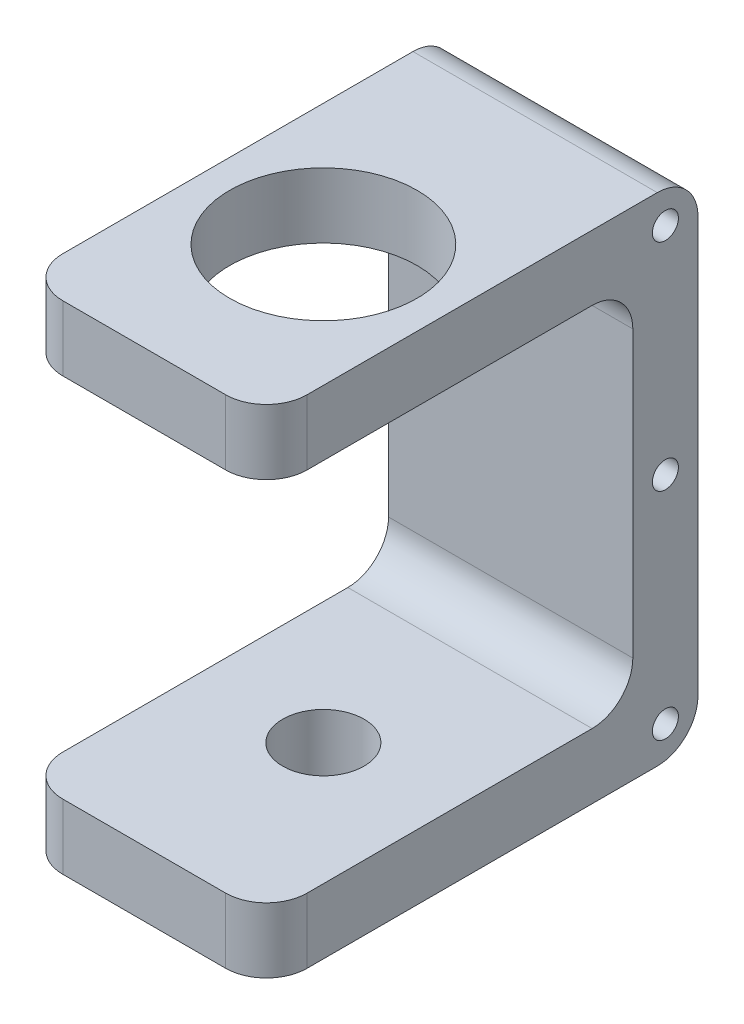
SolidWorks part; units mm, degrees
ref_plane "Front Plane" through (0, 0, 0) normal (0, 0, 1) x (1, 0, 0)
ref_plane "Top Plane" through (0, 0, 0) normal (0, 1, 0) x (1, 0, 0)
ref_plane "Right Plane" through (0, 0, 0) normal (1, 0, 0) x (0, 0, -1)
sketch "Sketch1" plane through (0, 0, 0) normal (1, 0, 0) x (0, 0, -1)
  line L0 (0, 0) -> (45, 0)
  line L1 (45, 0) -> (45, -45)
  line L2 (45, -45) -> (0, -45)
  line L3 (0, -45) -> (0, -53)
  line L4 (0, -53) -> (53, -53)
  line L5 (53, -53) -> (53, 8)
  line L6 (53, 8) -> (0, 8)
  line L7 (0, 8) -> (0, 0)
  point P2 (0, 0)
  point P9 (53.3766, -53)
  dimension "D1" = 45
  dimension "D2" = 45
  dimension "D3" = 8
  dimension "D4" = 8
extrude "Boss-Extrude1" add sketch "Sketch1" along normal blind 30 contours L0 L1 L2 L3 L4 L5 L6 L7
sketch "Sketch2" plane through (0, 8, 0) normal (0, 1, 0) x (1, 0, 0)
  line L0 (30, 0) -> (0, 0) construction
  circle A0 centre (15, 22) radius 11.5
  point P2 (15, 0)
  point P3 (0, 0)
  dimension "D1" = 23
  dimension "D2" = 22
extrude "Cut-Extrude1" cut sketch "Sketch2" against normal up to next
sketch "Sketch3" plane through (0, -45, 0) normal (0, 1, 0) x (1, 0, 0)
  circle A0 centre (15, 22) radius 5
  circle A1 centre (15, 22) radius 11.5 construction
  dimension "D1" = 10
extrude "Cut-Extrude2" cut sketch "Sketch3" against normal up to next contours A0
sketch "Sketch4" plane through (30, 0, 0) normal (1, 0, 0) x (0, 0, -1)
  line L0 (53, -53) -> (53, 8) construction
  line L1 (45, 0) -> (45, -45) construction
  line L2 (0, 0) -> (45, 0) construction
  line L3 (45, -45) -> (0, -45) construction
  circle A0 centre (49, 4) radius 1.6
  circle A1 centre (49, -49) radius 1.6
  circle A2 centre (49, -22.5) radius 1.6
  point P6 (53, -22.5)
  point P7 (0, 0)
  point P10 (0, 0)
  point P11 (0, 0)
  dimension "D1" = 3.2
  dimension "D2" = 4
  dimension "D3" = 4
  dimension "D4" = 4
extrude "Cut-Extrude3" cut sketch "Sketch4" against normal up to next contours A2 | A1 | A0
fillet "Fillet1" radius 5 6 edges at (15, -53, -53) (15, 8, -53) (0, -49, 0) (0, 4, 0) (30, -49, 0) (30, 4, 0)
fillet "Fillet2" radius 5 2 edges at (15, 0, -45) (15, -45, -45)
